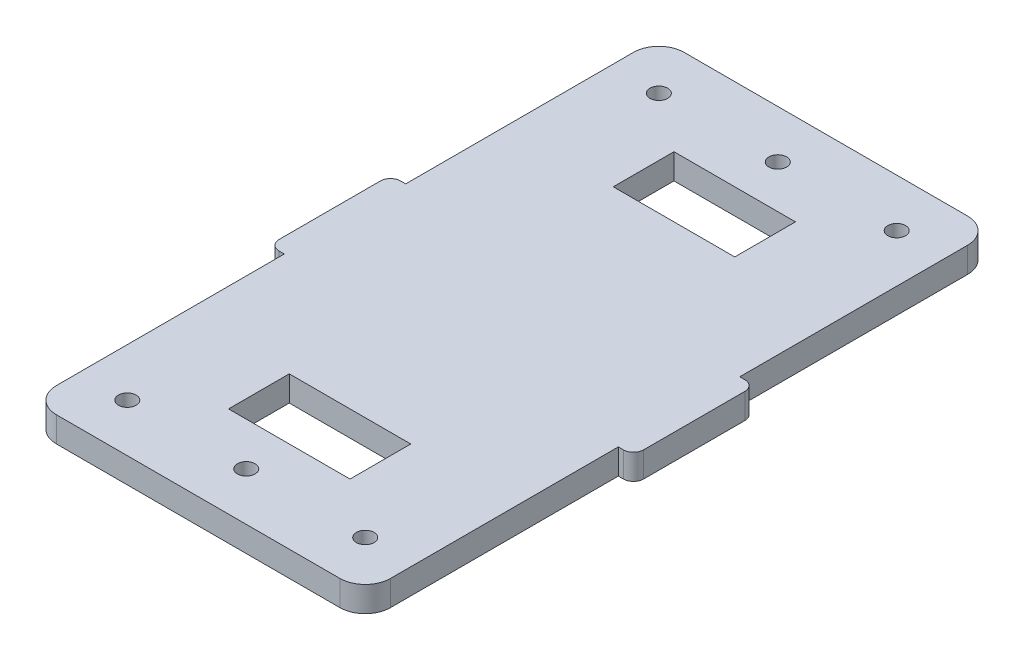
SolidWorks part; units mm, degrees
ref_plane "前视基准面" through (0, 0, 0) normal (0, 0, 1) x (1, 0, 0)
ref_plane "上视基准面" through (0, 0, 0) normal (0, 1, 0) x (1, 0, 0)
ref_plane "右视基准面" through (0, 0, 0) normal (1, 0, 0) x (0, 0, -1)
sketch "草图1" plane through (0, 0, 0) normal (0, 1, 0) x (1, 0, 0)
  line L1 (-36, 50) -> (36, 50)
  line L2 (-36, 50) -> (-36, -50)
  line L3 (-36, -50) -> (36, -50)
  line L4 (36, 50) -> (36, -50)
  line L5 (-36, 50) -> (36, -50) construction
  line L6 (-36, -50) -> (36, 50) construction
  point P0 (0, 0)
  dimension "D1" = 100
  dimension "D2" = 72
extrude "凸台-拉伸1" add sketch "草图1" along normal blind 5
sketch "草图2" plane through (0, 0, 50) normal (0, 0, 1) x (1, 0, 0)
  line L4 (-36, 0) -> (36, 0)
  line L5 (36, 0) -> (36, 5)
  line L6 (36, 5) -> (-36, 5)
  line L7 (-36, 5) -> (-36, 0)
  line L8 (-36, 0) -> (36, 0)
  line L9 (36, 0) -> (36, 5)
  line L10 (36, 5) -> (-36, 5)
  line L11 (-36, 5) -> (-36, 0)
  dimension "D1" = 0
extrude "凸台-拉伸2" add sketch "草图2" along normal blind 24
sketch "草图3" plane through (0, 5, 0) normal (0, 1, 0) x (1, 0, 0)
  line L1 (-36, 50) -> (-33, 50)
  line L2 (-36, 50) -> (-36, 0)
  line L3 (-36, 0) -> (-33, 0)
  line L4 (-33, 50) -> (-33, 0)
  line L5 (36, 50) -> (33, 50)
  line L6 (36, 50) -> (36, 0)
  line L7 (36, 0) -> (33, 0)
  line L8 (33, 50) -> (33, 0)
  line L9 (-36, -74) -> (-33, -74)
  line L10 (-36, -74) -> (-36, -24)
  line L11 (-36, -24) -> (-33, -24)
  line L12 (-33, -74) -> (-33, -24)
  line L13 (36, -74) -> (33, -74)
  line L14 (36, -74) -> (36, -24)
  line L15 (36, -24) -> (33, -24)
  line L16 (33, -74) -> (33, -24)
  dimension "D1" = 50
  dimension "D2" = 3
  dimension "D3" = 3
  dimension "D4" = 50
  dimension "D5" = 3
  dimension "D6" = 3
extrude "切除-拉伸1" cut sketch "草图3" against normal through all both and the other way through all
sketch "草图5" plane through (0, 5, 0) normal (0, 1, 0) x (1, 0, 0)
  line L0 (33, 50) -> (-33, 50) construction
  line L1 (-33, 0) -> (-33, 50) construction
  circle A0 centre (-23.5, 40.5) radius 1.75
  dimension "D1" = 3.5
  dimension "D2" = 9.5
  dimension "D3" = 9.5
extrude "切除-拉伸2" cut sketch "草图5" against normal through all both and the other way through all
sketch "草图6" plane through (0, 5, 0) normal (0, 1, 0) x (1, 0, 0)
  line L0 (33, 50) -> (-33, 50) construction
  line L1 (33, 50) -> (33, 0) construction
  line L2 (-33, -74) -> (-33, -24) construction
  line L3 (33, -74) -> (-33, -74) construction
  line L4 (33, -24) -> (33, -74) construction
  circle A0 centre (23.5, 40.5) radius 1.75
  circle A1 centre (-23.5, -64.5) radius 1.75
  circle A2 centre (23.5, -64.5) radius 1.75
  dimension "D1" = 3.5
  dimension "D4" = 9.5
  dimension "D5" = 9.5
  dimension "D6" = 9.5
  dimension "D7" = 3.5
  dimension "D8" = 3.5
  dimension "D9" = 9.5
  dimension "D2" = 9.5
  dimension "D3" = 9.5
extrude "切除-拉伸3" cut sketch "草图6" against normal through all both and the other way through all
sketch "草图7" plane through (0, 5, 0) normal (0, 1, 0) x (1, 0, 0)
  line L1 (-12, -56) -> (12, -56)
  line L2 (-12, -56) -> (-12, -44)
  line L3 (-12, -44) -> (12, -44)
  line L4 (12, -56) -> (12, -44)
  line L5 (-12, 20) -> (12, 20)
  line L6 (-12, 20) -> (-12, 32)
  line L7 (-12, 32) -> (12, 32)
  line L8 (12, 20) -> (12, 32)
extrude "切除-拉伸4" cut sketch "草图7" against normal through all both and the other way through all
fillet "圆角1" radius 5 4 edges at (-33, 2.5, 74) (33, 2.5, 74) (33, 2.5, -50) (-33, 2.5, -50)
fillet "圆角2" radius 2 4 edges at (36, 2.5, 24) (36, 2.5, 0) (-36, 2.5, 24) (-36, 2.5, 0)
sketch "草图8" plane through (0, 5, 0) normal (0, 1, 0) x (1, 0, 0)
  line L0 (0, 50) -> (0, -74) construction
  line L1 (28, 50) -> (-28, 50) construction
  line L2 (28, -74) -> (-28, -74) construction
  circle A0 centre (0, 40.5) radius 1.75
  circle A1 centre (0, -64.5) radius 1.75
  dimension "D1" = 3.5
  dimension "D3" = 3.5
  dimension "D4" = 9.5
  dimension "D2" = 9.5
extrude "切除-拉伸5" cut sketch "草图8" against normal through all both and the other way through all
